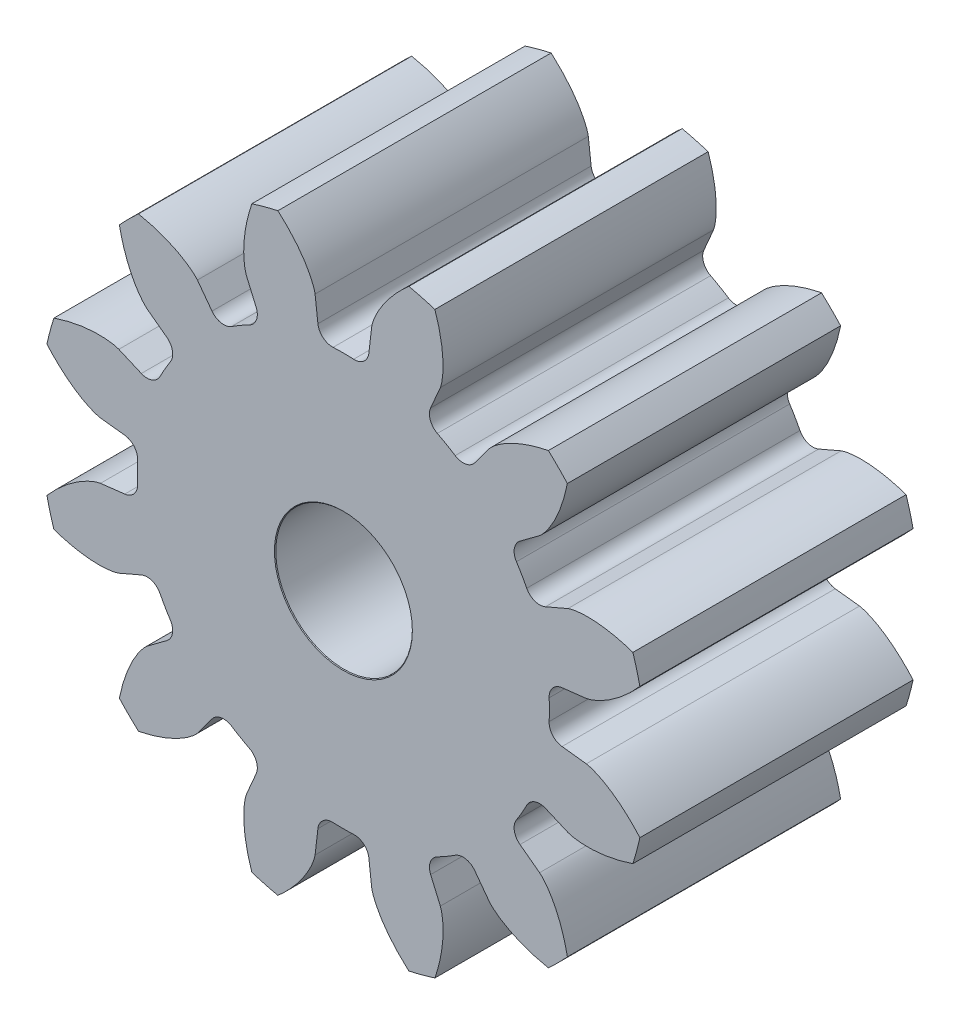
SolidWorks part; units mm, degrees
ref_plane "Front Plane" through (0, 0, 0) normal (0, 0, 1) x (1, 0, 0)
ref_plane "Top Plane" through (0, 0, 0) normal (0, 1, 0) x (1, 0, 0)
ref_plane "Right Plane" through (0, 0, 0) normal (1, 0, 0) x (0, 0, -1)
sketch "Sketch1" plane through (0, 0, 0) normal (0, 0, 1) x (1, 0, 0)
  line L0 (0, 0) -> (0, 9.525) construction
  line L1 (-3.0613, 10.6392) -> (3.0613, 8.4108) construction
  circle A0 centre (0, 0) radius 7.5406 construction
  circle A1 centre (0, 0) radius 11.1125 construction
  circle A2 centre (0, 0) radius 9.525 construction
  circle A3 centre (0, 0) radius 8.9506 construction
  point P8 (203.2, 0)
  point P13 (152.4, 0)
  dimension "OD | Outside Diameter" = 22.225
  dimension "Root Diameter" = 15.0812
  dimension "Gear Pitch Diameter" = 19.05
  dimension "Base Diameter" = 17.9011
  dimension "Pressure Angle" = 20
  dimension "Number of Teeth" = 304.8
  dimension "Gear Pitch | Diametral Pitch" = 406.4
sketch "Sketch2" plane through (0, 0, 0) normal (1, 0, 0) x (0, 0, -1)
  line L0 (-5, 0) -> (5, 0) construction
  point P2 (6.1125, 0)
  point P5 (11.6687, 0)
  point P6 (-6.1125, 0)
  dimension "Length" = 10
  dimension "D1" = 11.1125
  dimension "D2" = 16.6687
  dimension "D3" = 11.1125
sketch "Sketch3" plane through (0, 0, 0) normal (0, 0, 1) x (1, 0, 0)
  circle A0 centre (0, 0) radius 11.1125
  circle A1 centre (0, 0) radius 11.1125 construction
extrude "Boss-Extrude1" add sketch "Sketch3" against normal up to vertex (5 mm away) and the other way up to vertex (5 mm away) up to point (0, 0, -5) other way up to point (0, 0, 5)
sketch "Sketch4" plane through (0, 0, 0) normal (0, 0, 1) x (1, 0, 0)
  line L0 (0, 0) -> (7.49, 0.8727) construction
  line L2 (0, 0) -> (7.49, -0.8727) construction
  line L4 (7.49, 0.8727) -> (8.8904, 1.0359)
  line L5 (8.8904, -1.0359) -> (7.49, -0.8727)
  arc A0 (7.49, 0.8727) -> (7.49, -0.8727) centre (0, 0) cw
  arc A3 (10.8508, 2.3974) -> (10.8508, -2.3974) centre (0, 0) cw
  circle A4 centre (0, 0) radius 11.1125 construction
  spline S0 degree 4 poles (8.8904, 1.0359) (8.894, 1.0364) (8.9039, 1.0379) (8.9226, 1.0413) (8.953, 1.048) (8.9913, 1.0579) (9.0406, 1.0722) (9.0982, 1.0912) (9.1609, 1.1142) (9.2285, 1.1414) (9.2953, 1.1706) (9.3614, 1.2016) (9.4267, 1.2342) (9.505, 1.2755) (9.5979, 1.3278) (9.705, 1.3928) (9.8245, 1.4711) (9.9441, 1.5556) (10.06, 1.6428) (10.1748, 1.7352) (10.2843, 1.8278) (10.3956, 1.9283) (10.4972, 2.0234) (10.6081, 2.1347) (10.6968, 2.226) (10.8106, 2.3513) (10.8769, 2.4268) (10.9534, 2.5168) (10.9867, 2.5577) (11.0073, 2.5829) knots 0 0 0 0 0 0.005377 0.015084 0.028532 0.04661 0.064855 0.092111 0.119476 0.146842 0.174209 0.201575 0.228941 0.256307 0.307035 0.361767 0.4165 0.471232 0.525964 0.580697 0.635429 0.690161 0.744894 0.799626 0.854358 0.909091 0.954545 1 1 1 1 1 construction
  spline S1 degree 4 poles (8.8904, 1.0359) (8.894, 1.0364) (8.9039, 1.0379) (8.9226, 1.0413) (8.953, 1.048) (8.9913, 1.0579) (9.0406, 1.0722) (9.0982, 1.0912) (9.1609, 1.1142) (9.2285, 1.1414) (9.2953, 1.1706) (9.3614, 1.2016) (9.4267, 1.2342) (9.505, 1.2755) (9.5979, 1.3278) (9.705, 1.3928) (9.8245, 1.4711) (9.9441, 1.5556) (10.06, 1.6428) (10.1748, 1.7352) (10.2843, 1.8278) (10.3956, 1.9283) (10.4972, 2.0234) (10.6081, 2.1347) (10.6968, 2.226) (10.7859, 2.3241) (10.829, 2.3725) (10.8508, 2.3974) knots 0 0 0 0 0 0.005377 0.015084 0.028532 0.04661 0.064855 0.092111 0.119476 0.146842 0.174209 0.201575 0.228941 0.256307 0.307035 0.361767 0.4165 0.471232 0.525964 0.580697 0.635429 0.690161 0.744894 0.799626 0.854358 0.909091 0.909091 0.909091 0.909091 0.909091
  spline S2 degree 4 poles (8.8904, -1.0359) (8.894, -1.0364) (8.9039, -1.0379) (8.9226, -1.0413) (8.953, -1.048) (8.9913, -1.0579) (9.0406, -1.0722) (9.0982, -1.0912) (9.1609, -1.1142) (9.2285, -1.1414) (9.2953, -1.1706) (9.3614, -1.2016) (9.4267, -1.2342) (9.505, -1.2755) (9.5979, -1.3278) (9.705, -1.3928) (9.8245, -1.4711) (9.9441, -1.5556) (10.06, -1.6428) (10.1748, -1.7352) (10.2843, -1.8278) (10.3956, -1.9283) (10.4972, -2.0234) (10.6081, -2.1347) (10.6968, -2.226) (10.8106, -2.3513) (10.8769, -2.4268) (10.9534, -2.5168) (10.9867, -2.5577) (11.0073, -2.5829) knots 0 0 0 0 0 0.005377 0.015084 0.028532 0.04661 0.064855 0.092111 0.119476 0.146842 0.174209 0.201575 0.228941 0.256307 0.307035 0.361767 0.4165 0.471232 0.525964 0.580697 0.635429 0.690161 0.744894 0.799626 0.854358 0.909091 0.954545 1 1 1 1 1 construction
  spline S3 degree 4 poles (8.8904, -1.0359) (8.894, -1.0364) (8.9039, -1.0379) (8.9226, -1.0413) (8.953, -1.048) (8.9913, -1.0579) (9.0406, -1.0722) (9.0982, -1.0912) (9.1609, -1.1142) (9.2285, -1.1414) (9.2953, -1.1706) (9.3614, -1.2016) (9.4267, -1.2342) (9.505, -1.2755) (9.5979, -1.3278) (9.705, -1.3928) (9.8245, -1.4711) (9.9441, -1.5556) (10.06, -1.6428) (10.1748, -1.7352) (10.2843, -1.8278) (10.3956, -1.9283) (10.4972, -2.0234) (10.6081, -2.1347) (10.6968, -2.226) (10.7859, -2.3241) (10.829, -2.3725) (10.8508, -2.3974) knots 0 0 0 0 0 0.005377 0.015084 0.028532 0.04661 0.064855 0.092111 0.119476 0.146842 0.174209 0.201575 0.228941 0.256307 0.307035 0.361767 0.4165 0.471232 0.525964 0.580697 0.635429 0.690161 0.744894 0.799626 0.854358 0.909091 0.909091 0.909091 0.909091 0.909091
  dimension "D1" = 15.0812
extrude "Cut-Extrude1" cut sketch "Sketch4" against normal through all both and the other way through all
fillet "Fillet1" radius 0.5326 2 edges at (7.49, -0.8727, 0) (7.49, 0.8727, 0)
pattern_circular "CirPattern1" count 12 over 360 about axis through (0, 0, 5) along (0, 0, -1) of "Cut-Extrude1", "Fillet1"
sketch "Sketch5" plane through (0, 0, 5) normal (0, 0, 1) x (1, 0, 0)
  point P0 (0, 0)
hole_wizard "Ø5.0mm Dowel Hole1" positions "Sketch5" profile "Sketch6" hole size "Ø5.0" standard "ANSI Metric" end condition through all
sketch "Sketch6" plane through (0, 0, 5) normal (1, 0, 0) x (0, -1, 0)
  line L0 (0, 0) -> (0, 10)
  line L1 (0, 10) -> (2.5, 10)
  line L2 (2.5, 10) -> (2.5, 0.025)
  line L3 (2.5, 0.025) -> (2.525, 0)
  line L5 (2.525, 0) -> (0, 0)
  line L6 (-2.5, 0.025) -> (-2.525, 0) construction
  line L11 (0, -6.35) -> (0, 107.95) construction
  dimension "Thru Hole Dia." = 5
  dimension "Thru Hole Depth" = 10
  dimension "Near C'Sink Dia." = 5.05
  dimension "Near C'Sink Angle" = 90
equation "\"Root Diameter@Sketch1\"=\"Root Diameter\""
equation "\"OD | Outside Diameter@Sketch1\"=\"Outside Diameter\""
equation "\"D1@CirPattern1\"=\"Number of Teeth\""
equation "\"Diametral Pitch\"= 16"
equation "\"Number of Teeth\"=12"
equation "\"Pressure Angle\"=20"
equation "\"Pitch Diameter\"= \"Number of Teeth\" / \"Diametral Pitch\""
equation "\"Base Diameter\"= \"Pitch Diameter\" * cos ( \"Pressure Angle\" )"
equation "\"Outside Diameter\"= ( \"Number of Teeth\" + 2 ) / \"Diametral Pitch\""
equation "\"Dedendum\"= 1.25 / \"Diametral Pitch\""
equation "\"Root Diameter\"= \"Pitch Diameter\" - ( 2 * \"Dedendum\" )"
equation "\"Pitch Angle\"= 360deg / \"Number of Teeth\""
equation "\"Alpha\"= sqr ( \"Pitch Diameter\" ^ 2 - \"Base Diameter\" ^ 2 ) / \"Base Diameter\" * 180 / PI - \"Pressure Angle\""
equation "\"Beta\"= ( \"Pitch Angle\" / 4 - \"Alpha\" )"
equation "\"Phi\"= sqr ( ( \"Outside Diameter\" / 2 ) ^ 2 - ( \"Base Diameter\" / 2 ) ^ 2 ) / ( \"Base Diameter\" / 2 )"
equation "\"Addendum\"= 1 / \"Diametral Pitch\""
equation "\"WorkingDepth\"= 2 / \"Diametral Pitch\""
equation "\"WholeDepth\"= 2.25 / \"Diametral Pitch\""
equation "\"Clearance\"= 0.25 / \"Diametral Pitch\""
equation "\"ToothThickness\"= ( pi * 2 ) / \"Diametral Pitch\""
equation "\"CircularPitch\"= pi / \"Diametral Pitch\""
equation "\"Number of Teeth@Sketch1\"=\"Number of Teeth\""
equation "\"Gear Pitch | Diametral Pitch@Sketch1\"=\"Diametral Pitch\""
equation "\"Pressure Angle@Sketch1\"=\"Pressure Angle\""
equation "\"Gear Pitch Diameter@Sketch1\"=\"Pitch Diameter\""
equation "\"Base Diameter@Sketch1\"=\"Base Diameter\""
equation "\"Fillet\"= \"Clearance\" * cos ( \"Pressure Angle\" ) * tan ( ( 90 + \"Pressure Angle\" ) / 2 )"
equation "\"D1@Fillet1\"=\"Fillet\""
equation "\"D1@Sketch4\"=if( \"Base Diameter\">\"Root Diameter\",\"Root Diameter\",\"Base Diameter\"-.00001)"
equation "\"D1@Sketch2\"=\"OD | Outside Diameter@Sketch1\"*2*0.5*0.5"
equation "\"D2@Sketch2\"=\"D1@Sketch2\"*1.5"
equation "\"D3@Sketch2\"=\"D1@Sketch2\""
equation "\"Length\"= 1cm"
equation "\"Length@Sketch2\"= \"Length\""
